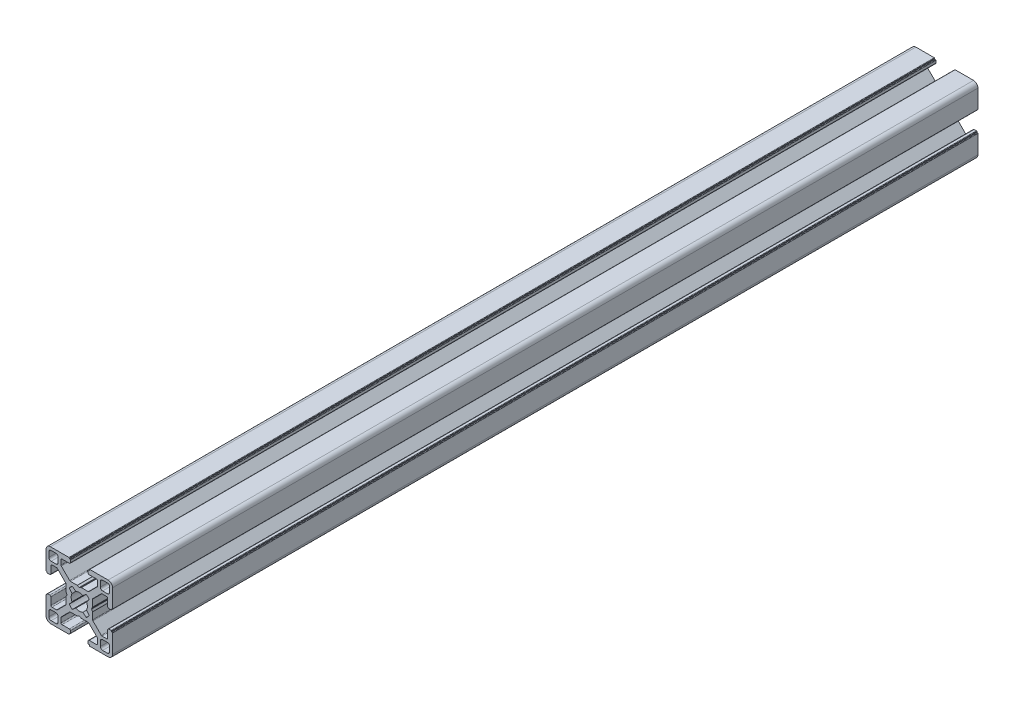
SolidWorks part; units mm, degrees
ref_plane "Alzado" through (0, 0, 0) normal (0, 0, 1) x (1, 0, 0)
ref_plane "Planta" through (0, 0, 0) normal (0, 1, 0) x (1, 0, 0)
ref_plane "Vista lateral" through (0, 0, 0) normal (1, 0, 0) x (0, 0, -1)
ref_plane "Plano1" through (0, 0, 1000) normal (0, 0, 1) x (1, 0, 0)
sketch "Croquis1" plane through (0, 0, 1000) normal (0, 0, 1) x (1, 0, 0)
  line L0 (8, -5.5) -> (5.8, -5.5)
  line L1 (4.8, -4.5) -> (4.8, -2.3)
  line L2 (5.8, -1.3) -> (8, -1.3)
  line L3 (9, -2.3) -> (9, -4.5)
  line L4 (-15.2, -5.5) -> (-17.4, -5.5)
  line L5 (-18.4, -4.5) -> (-18.4, -2.3)
  line L6 (-17.4, -1.3) -> (-15.2, -1.3)
  line L7 (-14.2, -2.3) -> (-14.2, -4.5)
  line L8 (-17.4, -24.5) -> (-15.2, -24.5)
  line L9 (-14.2, -25.5) -> (-14.2, -27.7)
  line L10 (-15.2, -28.7) -> (-17.4, -28.7)
  line L11 (-18.4, -27.7) -> (-18.4, -25.5)
  line L12 (5.8, -24.5) -> (8, -24.5)
  line L13 (9, -25.5) -> (9, -27.7)
  line L14 (8, -28.7) -> (5.8, -28.7)
  line L15 (4.8, -27.7) -> (4.8, -25.5)
  line L16 (-7.8359, -10.4816) -> (-6.3001, -11.7194)
  line L17 (-3.0999, -11.7194) -> (-1.5641, -10.4816)
  line L18 (-0.1947, -11.8453) -> (-1.4194, -13.3999)
  line L19 (-1.4194, -16.6001) -> (-0.1947, -18.1547)
  line L20 (-1.5641, -19.5184) -> (-3.0999, -18.2806)
  line L21 (-6.3001, -18.2806) -> (-7.8359, -19.5184)
  line L22 (-9.2053, -18.1547) -> (-7.9806, -16.6001)
  line L23 (-7.9806, -13.3999) -> (-9.2053, -11.8453)
  line L24 (9.8, -10.5) -> (10.1, -10.5)
  line L25 (10.3, -10.3) -> (10.3, -2)
  line L26 (8.3, 0) -> (0, 0)
  line L27 (-0.2, -0.2) -> (-0.2, -0.5)
  line L28 (-0.2, -0.5) -> (-0.5, -0.5)
  line L29 (-0.7, -0.7) -> (-0.7, -1.7)
  line L30 (-0.2, -2.2) -> (3.05, -2.2)
  line L31 (3.55, -2.7) -> (3.55, -4.7431)
  line L32 (3.4037, -5.0964) -> (-0.3491, -8.8534)
  line L33 (-0.7028, -9) -> (-3.7468, -9)
  line L34 (-3.8462, -9.0264) -> (-4.6006, -9.4583)
  line L35 (-4.7994, -9.4583) -> (-5.5538, -9.0264)
  line L36 (-5.6532, -9) -> (-8.6972, -9)
  line L37 (-9.0509, -8.8534) -> (-12.8037, -5.0964)
  line L38 (-12.95, -4.7431) -> (-12.95, -2.7)
  line L39 (-12.45, -2.2) -> (-9.2, -2.2)
  line L40 (-8.7, -1.7) -> (-8.7, -0.7)
  line L41 (-8.9, -0.5) -> (-9.2, -0.5)
  line L42 (-9.2, -0.5) -> (-9.2, -0.2)
  line L43 (-9.4, 0) -> (-17.7, 0)
  line L44 (-19.7, -2) -> (-19.7, -10.3)
  line L45 (-19.5, -10.5) -> (-19.2, -10.5)
  line L46 (-19.2, -10.5) -> (-19.2, -10.8)
  line L47 (-19, -11) -> (-18, -11)
  line L48 (-17.5, -10.5) -> (-17.5, -7.25)
  line L49 (-17, -6.75) -> (-14.9569, -6.75)
  line L50 (-14.6036, -6.8963) -> (-10.8466, -10.6491)
  line L51 (-10.7, -11.0028) -> (-10.7, -14.0468)
  line L52 (-10.6736, -14.1462) -> (-10.2417, -14.9006)
  line L53 (-10.2417, -15.0994) -> (-10.6736, -15.8538)
  line L54 (-10.7, -15.9532) -> (-10.7, -18.9972)
  line L55 (-10.8466, -19.3509) -> (-14.6036, -23.1037)
  line L56 (-14.9569, -23.25) -> (-17, -23.25)
  line L57 (-17.5, -22.75) -> (-17.5, -19.5)
  line L58 (-18, -19) -> (-19, -19)
  line L59 (-19.2, -19.2) -> (-19.2, -19.5)
  line L60 (-19.2, -19.5) -> (-19.5, -19.5)
  line L61 (-19.7, -19.7) -> (-19.7, -28)
  line L62 (-17.7, -30) -> (-9.4, -30)
  line L63 (-9.2, -29.8) -> (-9.2, -29.5)
  line L64 (-9.2, -29.5) -> (-8.9, -29.5)
  line L65 (-8.7, -29.3) -> (-8.7, -28.3)
  line L66 (-9.2, -27.8) -> (-12.45, -27.8)
  line L67 (-12.95, -27.3) -> (-12.95, -25.2569)
  line L68 (-12.8037, -24.9036) -> (-9.0509, -21.1466)
  line L69 (-8.6972, -21) -> (-5.6532, -21)
  line L70 (-5.5538, -20.9736) -> (-4.7994, -20.5417)
  line L71 (-4.6006, -20.5417) -> (-3.8462, -20.9736)
  line L72 (-3.7468, -21) -> (-0.7028, -21)
  line L73 (-0.3491, -21.1466) -> (3.4037, -24.9036)
  line L74 (3.55, -25.2569) -> (3.55, -27.3)
  line L75 (3.05, -27.8) -> (-0.2, -27.8)
  line L76 (-0.7, -28.3) -> (-0.7, -29.3)
  line L77 (-0.5, -29.5) -> (-0.2, -29.5)
  line L78 (-0.2, -29.5) -> (-0.2, -29.8)
  line L79 (0, -30) -> (8.3, -30)
  line L80 (10.3, -28) -> (10.3, -19.7)
  line L81 (10.1, -19.5) -> (9.8, -19.5)
  line L82 (9.8, -19.5) -> (9.8, -19.2)
  line L83 (9.6, -19) -> (8.6, -19)
  line L84 (8.1, -19.5) -> (8.1, -22.75)
  line L85 (7.6, -23.25) -> (5.5569, -23.25)
  line L86 (5.2036, -23.1037) -> (1.4466, -19.3509)
  line L87 (1.3, -18.9972) -> (1.3, -15.9532)
  line L88 (1.2736, -15.8538) -> (0.8417, -15.0994)
  line L89 (0.8417, -14.9006) -> (1.2736, -14.1462)
  line L90 (1.3, -14.0468) -> (1.3, -11.0028)
  line L91 (1.4466, -10.6491) -> (5.2036, -6.8963)
  line L92 (5.5569, -6.75) -> (7.6, -6.75)
  line L93 (8.1, -7.25) -> (8.1, -10.5)
  line L94 (8.6, -11) -> (9.6, -11)
  line L95 (9.8, -10.8) -> (9.8, -10.5)
  arc A0 (9, -4.5) -> (8, -5.5) centre (8, -4.5) cw
  arc A1 (5.8, -5.5) -> (4.8, -4.5) centre (5.8, -4.5) cw
  arc A2 (4.8, -2.3) -> (5.8, -1.3) centre (5.8, -2.3) cw
  arc A3 (8, -1.3) -> (9, -2.3) centre (8, -2.3) cw
  arc A4 (-14.2, -4.5) -> (-15.2, -5.5) centre (-15.2, -4.5) cw
  arc A5 (-17.4, -5.5) -> (-18.4, -4.5) centre (-17.4, -4.5) cw
  arc A6 (-18.4, -2.3) -> (-17.4, -1.3) centre (-17.4, -2.3) cw
  arc A7 (-15.2, -1.3) -> (-14.2, -2.3) centre (-15.2, -2.3) cw
  arc A8 (-18.4, -25.5) -> (-17.4, -24.5) centre (-17.4, -25.5) cw
  arc A9 (-15.2, -24.5) -> (-14.2, -25.5) centre (-15.2, -25.5) cw
  arc A10 (-14.2, -27.7) -> (-15.2, -28.7) centre (-15.2, -27.7) cw
  arc A11 (-17.4, -28.7) -> (-18.4, -27.7) centre (-17.4, -27.7) cw
  arc A12 (4.8, -25.5) -> (5.8, -24.5) centre (5.8, -25.5) cw
  arc A13 (8, -24.5) -> (9, -25.5) centre (8, -25.5) cw
  arc A14 (9, -27.7) -> (8, -28.7) centre (8, -27.7) cw
  arc A15 (5.8, -28.7) -> (4.8, -27.7) centre (5.8, -27.7) cw
  arc A16 (-9.2053, -11.8453) -> (-7.8359, -10.4816) centre (-4.7, -15) cw
  arc A17 (-6.3001, -11.7194) -> (-3.0999, -11.7194) centre (-4.7, -15) cw
  arc A18 (-1.5641, -10.4816) -> (-0.1947, -11.8453) centre (-4.7, -15) cw
  arc A19 (-1.4194, -13.3999) -> (-1.4194, -16.6001) centre (-4.7, -15) cw
  arc A20 (-0.1947, -18.1547) -> (-1.5641, -19.5184) centre (-4.7, -15) cw
  arc A21 (-3.0999, -18.2806) -> (-6.3001, -18.2806) centre (-4.7, -15) cw
  arc A22 (-7.8359, -19.5184) -> (-9.2053, -18.1547) centre (-4.7, -15) cw
  arc A23 (-7.9806, -16.6001) -> (-7.9806, -13.3999) centre (-4.7, -15) cw
  arc A24 (10.1, -10.5) -> (10.3, -10.3) centre (10.1, -10.3) ccw
  arc A25 (10.3, -2) -> (8.3, 0) centre (8.3, -2) ccw
  arc A26 (0, 0) -> (-0.2, -0.2) centre (0, -0.2) ccw
  arc A27 (-0.5, -0.5) -> (-0.7, -0.7) centre (-0.5, -0.7) ccw
  arc A28 (-0.7, -1.7) -> (-0.2, -2.2) centre (-0.2, -1.7) ccw
  arc A29 (3.05, -2.2) -> (3.55, -2.7) centre (3.05, -2.7) cw
  arc A30 (3.55, -4.7431) -> (3.4037, -5.0964) centre (3.05, -4.7431) cw
  arc A31 (-0.3491, -8.8534) -> (-0.7028, -9) centre (-0.7028, -8.5) cw
  arc A32 (-3.7468, -9) -> (-3.8462, -9.0264) centre (-3.7468, -9.2) ccw
  arc A33 (-4.6006, -9.4583) -> (-4.7994, -9.4583) centre (-4.7, -9.2847) cw
  arc A34 (-5.5538, -9.0264) -> (-5.6532, -9) centre (-5.6532, -9.2) ccw
  arc A35 (-8.6972, -9) -> (-9.0509, -8.8534) centre (-8.6972, -8.5) cw
  arc A36 (-12.8037, -5.0964) -> (-12.95, -4.7431) centre (-12.45, -4.7431) cw
  arc A37 (-12.95, -2.7) -> (-12.45, -2.2) centre (-12.45, -2.7) cw
  arc A38 (-9.2, -2.2) -> (-8.7, -1.7) centre (-9.2, -1.7) ccw
  arc A39 (-8.7, -0.7) -> (-8.9, -0.5) centre (-8.9, -0.7) ccw
  arc A40 (-9.2, -0.2) -> (-9.4, 0) centre (-9.4, -0.2) ccw
  arc A41 (-17.7, 0) -> (-19.7, -2) centre (-17.7, -2) ccw
  arc A42 (-19.7, -10.3) -> (-19.5, -10.5) centre (-19.5, -10.3) ccw
  arc A43 (-19.2, -10.8) -> (-19, -11) centre (-19, -10.8) ccw
  arc A44 (-18, -11) -> (-17.5, -10.5) centre (-18, -10.5) ccw
  arc A45 (-17.5, -7.25) -> (-17, -6.75) centre (-17, -7.25) cw
  arc A46 (-14.9569, -6.75) -> (-14.6036, -6.8963) centre (-14.9569, -7.25) cw
  arc A47 (-10.8466, -10.6491) -> (-10.7, -11.0028) centre (-11.2, -11.0028) cw
  arc A48 (-10.7, -14.0468) -> (-10.6736, -14.1462) centre (-10.5, -14.0468) ccw
  arc A49 (-10.2417, -14.9006) -> (-10.2417, -15.0994) centre (-10.4153, -15) cw
  arc A50 (-10.6736, -15.8538) -> (-10.7, -15.9532) centre (-10.5, -15.9532) ccw
  arc A51 (-10.7, -18.9972) -> (-10.8466, -19.3509) centre (-11.2, -18.9972) cw
  arc A52 (-14.6036, -23.1037) -> (-14.9569, -23.25) centre (-14.9569, -22.75) cw
  arc A53 (-17, -23.25) -> (-17.5, -22.75) centre (-17, -22.75) cw
  arc A54 (-17.5, -19.5) -> (-18, -19) centre (-18, -19.5) ccw
  arc A55 (-19, -19) -> (-19.2, -19.2) centre (-19, -19.2) ccw
  arc A56 (-19.5, -19.5) -> (-19.7, -19.7) centre (-19.5, -19.7) ccw
  arc A57 (-19.7, -28) -> (-17.7, -30) centre (-17.7, -28) ccw
  arc A58 (-9.4, -30) -> (-9.2, -29.8) centre (-9.4, -29.8) ccw
  arc A59 (-8.9, -29.5) -> (-8.7, -29.3) centre (-8.9, -29.3) ccw
  arc A60 (-8.7, -28.3) -> (-9.2, -27.8) centre (-9.2, -28.3) ccw
  arc A61 (-12.45, -27.8) -> (-12.95, -27.3) centre (-12.45, -27.3) cw
  arc A62 (-12.95, -25.2569) -> (-12.8037, -24.9036) centre (-12.45, -25.2569) cw
  arc A63 (-9.0509, -21.1466) -> (-8.6972, -21) centre (-8.6972, -21.5) cw
  arc A64 (-5.6532, -21) -> (-5.5538, -20.9736) centre (-5.6532, -20.8) ccw
  arc A65 (-4.7994, -20.5417) -> (-4.6006, -20.5417) centre (-4.7, -20.7153) cw
  arc A66 (-3.8462, -20.9736) -> (-3.7468, -21) centre (-3.7468, -20.8) ccw
  arc A67 (-0.7028, -21) -> (-0.3491, -21.1466) centre (-0.7028, -21.5) cw
  arc A68 (3.4037, -24.9036) -> (3.55, -25.2569) centre (3.05, -25.2569) cw
  arc A69 (3.55, -27.3) -> (3.05, -27.8) centre (3.05, -27.3) cw
  arc A70 (-0.2, -27.8) -> (-0.7, -28.3) centre (-0.2, -28.3) ccw
  arc A71 (-0.7, -29.3) -> (-0.5, -29.5) centre (-0.5, -29.3) ccw
  arc A72 (-0.2, -29.8) -> (0, -30) centre (0, -29.8) ccw
  arc A73 (8.3, -30) -> (10.3, -28) centre (8.3, -28) ccw
  arc A74 (10.3, -19.7) -> (10.1, -19.5) centre (10.1, -19.7) ccw
  arc A75 (9.8, -19.2) -> (9.6, -19) centre (9.6, -19.2) ccw
  arc A76 (8.6, -19) -> (8.1, -19.5) centre (8.6, -19.5) ccw
  arc A77 (8.1, -22.75) -> (7.6, -23.25) centre (7.6, -22.75) cw
  arc A78 (5.5569, -23.25) -> (5.2036, -23.1037) centre (5.5569, -22.75) cw
  arc A79 (1.4466, -19.3509) -> (1.3, -18.9972) centre (1.8, -18.9972) cw
  arc A80 (1.3, -15.9532) -> (1.2736, -15.8538) centre (1.1, -15.9532) ccw
  arc A81 (0.8417, -15.0994) -> (0.8417, -14.9006) centre (1.0153, -15) cw
  arc A82 (1.2736, -14.1462) -> (1.3, -14.0468) centre (1.1, -14.0468) ccw
  arc A83 (1.3, -11.0028) -> (1.4466, -10.6491) centre (1.8, -11.0028) cw
  arc A84 (5.2036, -6.8963) -> (5.5569, -6.75) centre (5.5569, -7.25) cw
  arc A85 (7.6, -6.75) -> (8.1, -7.25) centre (7.6, -7.25) cw
  arc A86 (8.1, -10.5) -> (8.6, -11) centre (8.6, -10.5) ccw
  arc A87 (9.6, -11) -> (9.8, -10.8) centre (9.6, -10.8) ccw
extrude "Saliente-Extruir1" add sketch "Croquis1" against normal blind 1000
sketch "Croquis4" plane through (0, 0, 0) normal (0, 0, -1) x (-1, 0, 0)
  line L72 (-9.8, -10.5) -> (-9.8, -10.8)
  line L73 (-9.6, -11) -> (-8.6, -11)
  line L74 (-8.1, -10.5) -> (-8.1, -7.25)
  line L75 (-7.6, -6.75) -> (-5.5569, -6.75)
  line L76 (-5.2036, -6.8963) -> (-1.4466, -10.6491)
  line L77 (-1.3, -11.0028) -> (-1.3, -14.0468)
  line L78 (-1.2736, -14.1462) -> (-0.8417, -14.9006)
  line L79 (-0.8417, -15.0994) -> (-1.2736, -15.8538)
  line L80 (-1.3, -15.9532) -> (-1.3, -18.9972)
  line L81 (-1.4466, -19.3509) -> (-5.2036, -23.1037)
  line L82 (-5.5569, -23.25) -> (-7.6, -23.25)
  line L83 (-8.1, -22.75) -> (-8.1, -19.5)
  line L84 (-8.6, -19) -> (-9.6, -19)
  line L85 (-9.8, -19.2) -> (-9.8, -19.5)
  line L86 (-9.8, -19.5) -> (-10.1, -19.5)
  line L87 (-10.3, -19.7) -> (-10.3, -28)
  line L88 (-8.3, -30) -> (0, -30)
  line L89 (0.2, -29.8) -> (0.2, -29.5)
  line L90 (0.2, -29.5) -> (0.5, -29.5)
  line L91 (0.7, -29.3) -> (0.7, -28.3)
  line L92 (0.2, -27.8) -> (-3.05, -27.8)
  line L93 (-3.55, -27.3) -> (-3.55, -25.2569)
  line L94 (-3.4037, -24.9036) -> (0.3491, -21.1466)
  line L95 (0.7028, -21) -> (3.7468, -21)
  line L96 (3.8462, -20.9736) -> (4.6006, -20.5417)
  line L97 (4.7994, -20.5417) -> (5.5538, -20.9736)
  line L98 (5.6532, -21) -> (8.6972, -21)
  line L99 (9.0509, -21.1466) -> (12.8037, -24.9036)
  line L100 (12.95, -25.2569) -> (12.95, -27.3)
  line L101 (12.45, -27.8) -> (9.2, -27.8)
  line L102 (8.7, -28.3) -> (8.7, -29.3)
  line L103 (8.9, -29.5) -> (9.2, -29.5)
  line L104 (9.2, -29.5) -> (9.2, -29.8)
  line L105 (9.4, -30) -> (17.7, -30)
  line L106 (19.7, -28) -> (19.7, -19.7)
  line L107 (19.5, -19.5) -> (19.2, -19.5)
  line L108 (19.2, -19.5) -> (19.2, -19.2)
  line L109 (19, -19) -> (18, -19)
  line L110 (17.5, -19.5) -> (17.5, -22.75)
  line L111 (17, -23.25) -> (14.9569, -23.25)
  line L112 (14.6036, -23.1037) -> (10.8466, -19.3509)
  line L113 (10.7, -18.9972) -> (10.7, -15.9532)
  line L114 (10.6736, -15.8538) -> (10.2417, -15.0994)
  line L115 (10.2417, -14.9006) -> (10.6736, -14.1462)
  line L116 (10.7, -14.0468) -> (10.7, -11.0028)
  line L117 (10.8466, -10.6491) -> (14.6036, -6.8963)
  line L118 (14.9569, -6.75) -> (17, -6.75)
  line L119 (17.5, -7.25) -> (17.5, -10.5)
  line L120 (18, -11) -> (19, -11)
  line L121 (19.2, -10.8) -> (19.2, -10.5)
  line L122 (19.2, -10.5) -> (19.5, -10.5)
  line L123 (19.7, -10.3) -> (19.7, -2)
  line L124 (17.7, 0) -> (9.4, 0)
  line L125 (9.2, -0.2) -> (9.2, -0.5)
  line L126 (9.2, -0.5) -> (8.9, -0.5)
  line L127 (8.7, -0.7) -> (8.7, -1.7)
  line L128 (9.2, -2.2) -> (12.45, -2.2)
  line L129 (12.95, -2.7) -> (12.95, -4.7431)
  line L130 (12.8037, -5.0964) -> (9.0509, -8.8534)
  line L131 (8.6972, -9) -> (5.6532, -9)
  line L132 (5.5538, -9.0264) -> (4.7994, -9.4583)
  line L133 (4.6006, -9.4583) -> (3.8462, -9.0264)
  line L134 (3.7468, -9) -> (0.7028, -9)
  line L135 (0.3491, -8.8534) -> (-3.4037, -5.0964)
  line L136 (-3.55, -4.7431) -> (-3.55, -2.7)
  line L137 (-3.05, -2.2) -> (0.2, -2.2)
  line L138 (0.7, -1.7) -> (0.7, -0.7)
  line L139 (0.5, -0.5) -> (0.2, -0.5)
  line L140 (0.2, -0.5) -> (0.2, -0.2)
  line L141 (0, 0) -> (-8.3, 0)
  line L142 (-10.3, -2) -> (-10.3, -10.3)
  line L143 (-10.1, -10.5) -> (-9.8, -10.5)
  line L144 (-9.8, -10.5) -> (-9.8, -10.8)
  line L145 (-9.6, -11) -> (-8.6, -11)
  line L146 (-8.1, -10.5) -> (-8.1, -7.25)
  line L147 (-7.6, -6.75) -> (-5.5569, -6.75)
  line L148 (-5.2036, -6.8963) -> (-1.4466, -10.6491)
  line L149 (-1.3, -11.0028) -> (-1.3, -14.0468)
  line L150 (-1.2736, -14.1462) -> (-0.8417, -14.9006)
  line L151 (-0.8417, -15.0994) -> (-1.2736, -15.8538)
  line L152 (-1.3, -15.9532) -> (-1.3, -18.9972)
  line L153 (-1.4466, -19.3509) -> (-5.2036, -23.1037)
  line L154 (-5.5569, -23.25) -> (-7.6, -23.25)
  line L155 (-8.1, -22.75) -> (-8.1, -19.5)
  line L156 (-8.6, -19) -> (-9.6, -19)
  line L157 (-9.8, -19.2) -> (-9.8, -19.5)
  line L158 (-9.8, -19.5) -> (-10.1, -19.5)
  line L159 (-10.3, -19.7) -> (-10.3, -28)
  line L160 (-8.3, -30) -> (0, -30)
  line L161 (0.2, -29.8) -> (0.2, -29.5)
  line L162 (0.2, -29.5) -> (0.5, -29.5)
  line L163 (0.7, -29.3) -> (0.7, -28.3)
  line L164 (0.2, -27.8) -> (-3.05, -27.8)
  line L165 (-3.55, -27.3) -> (-3.55, -25.2569)
  line L166 (-3.4037, -24.9036) -> (0.3491, -21.1466)
  line L167 (0.7028, -21) -> (3.7468, -21)
  line L168 (3.8462, -20.9736) -> (4.6006, -20.5417)
  line L169 (4.7994, -20.5417) -> (5.5538, -20.9736)
  line L170 (5.6532, -21) -> (8.6972, -21)
  line L171 (9.0509, -21.1466) -> (12.8037, -24.9036)
  line L172 (12.95, -25.2569) -> (12.95, -27.3)
  line L173 (12.45, -27.8) -> (9.2, -27.8)
  line L174 (8.7, -28.3) -> (8.7, -29.3)
  line L175 (8.9, -29.5) -> (9.2, -29.5)
  line L176 (9.2, -29.5) -> (9.2, -29.8)
  line L177 (9.4, -30) -> (17.7, -30)
  line L178 (19.7, -28) -> (19.7, -19.7)
  line L179 (19.5, -19.5) -> (19.2, -19.5)
  line L180 (19.2, -19.5) -> (19.2, -19.2)
  line L181 (19, -19) -> (18, -19)
  line L182 (17.5, -19.5) -> (17.5, -22.75)
  line L183 (17, -23.25) -> (14.9569, -23.25)
  line L184 (14.6036, -23.1037) -> (10.8466, -19.3509)
  line L185 (10.7, -18.9972) -> (10.7, -15.9532)
  line L186 (10.6736, -15.8538) -> (10.2417, -15.0994)
  line L187 (10.2417, -14.9006) -> (10.6736, -14.1462)
  line L188 (10.7, -14.0468) -> (10.7, -11.0028)
  line L189 (10.8466, -10.6491) -> (14.6036, -6.8963)
  line L190 (14.9569, -6.75) -> (17, -6.75)
  line L191 (17.5, -7.25) -> (17.5, -10.5)
  line L192 (18, -11) -> (19, -11)
  line L193 (19.2, -10.8) -> (19.2, -10.5)
  line L194 (19.2, -10.5) -> (19.5, -10.5)
  line L195 (19.7, -10.3) -> (19.7, -2)
  line L196 (17.7, 0) -> (9.4, 0)
  line L197 (9.2, -0.2) -> (9.2, -0.5)
  line L198 (9.2, -0.5) -> (8.9, -0.5)
  line L199 (8.7, -0.7) -> (8.7, -1.7)
  line L200 (9.2, -2.2) -> (12.45, -2.2)
  line L201 (12.95, -2.7) -> (12.95, -4.7431)
  line L202 (12.8037, -5.0964) -> (9.0509, -8.8534)
  line L203 (8.6972, -9) -> (5.6532, -9)
  line L204 (5.5538, -9.0264) -> (4.7994, -9.4583)
  line L205 (4.6006, -9.4583) -> (3.8462, -9.0264)
  line L206 (3.7468, -9) -> (0.7028, -9)
  line L207 (0.3491, -8.8534) -> (-3.4037, -5.0964)
  line L208 (-3.55, -4.7431) -> (-3.55, -2.7)
  line L209 (-3.05, -2.2) -> (0.2, -2.2)
  line L210 (0.7, -1.7) -> (0.7, -0.7)
  line L211 (0.5, -0.5) -> (0.2, -0.5)
  line L212 (0.2, -0.5) -> (0.2, -0.2)
  line L213 (0, 0) -> (-8.3, 0)
  line L214 (-10.3, -2) -> (-10.3, -10.3)
  line L215 (-10.1, -10.5) -> (-9.8, -10.5)
  arc A64 (-9.8, -10.8) -> (-9.6, -11) centre (-9.6, -10.8) ccw
  arc A65 (-8.6, -11) -> (-8.1, -10.5) centre (-8.6, -10.5) ccw
  arc A66 (-7.6, -6.75) -> (-8.1, -7.25) centre (-7.6, -7.25) ccw
  arc A67 (-5.2036, -6.8963) -> (-5.5569, -6.75) centre (-5.5569, -7.25) ccw
  arc A68 (-1.3, -11.0028) -> (-1.4466, -10.6491) centre (-1.8, -11.0028) ccw
  arc A69 (-1.3, -14.0468) -> (-1.2736, -14.1462) centre (-1.1, -14.0468) ccw
  arc A70 (-0.8417, -15.0994) -> (-0.8417, -14.9006) centre (-1.0153, -15) ccw
  arc A71 (-1.2736, -15.8538) -> (-1.3, -15.9532) centre (-1.1, -15.9532) ccw
  arc A72 (-1.4466, -19.3509) -> (-1.3, -18.9972) centre (-1.8, -18.9972) ccw
  arc A73 (-5.5569, -23.25) -> (-5.2036, -23.1037) centre (-5.5569, -22.75) ccw
  arc A74 (-8.1, -22.75) -> (-7.6, -23.25) centre (-7.6, -22.75) ccw
  arc A75 (-8.1, -19.5) -> (-8.6, -19) centre (-8.6, -19.5) ccw
  arc A76 (-9.6, -19) -> (-9.8, -19.2) centre (-9.6, -19.2) ccw
  arc A77 (-10.1, -19.5) -> (-10.3, -19.7) centre (-10.1, -19.7) ccw
  arc A78 (-10.3, -28) -> (-8.3, -30) centre (-8.3, -28) ccw
  arc A79 (0, -30) -> (0.2, -29.8) centre (0, -29.8) ccw
  arc A80 (0.5, -29.5) -> (0.7, -29.3) centre (0.5, -29.3) ccw
  arc A81 (0.7, -28.3) -> (0.2, -27.8) centre (0.2, -28.3) ccw
  arc A82 (-3.55, -27.3) -> (-3.05, -27.8) centre (-3.05, -27.3) ccw
  arc A83 (-3.4037, -24.9036) -> (-3.55, -25.2569) centre (-3.05, -25.2569) ccw
  arc A84 (0.7028, -21) -> (0.3491, -21.1466) centre (0.7028, -21.5) ccw
  arc A85 (3.7468, -21) -> (3.8462, -20.9736) centre (3.7468, -20.8) ccw
  arc A86 (4.7994, -20.5417) -> (4.6006, -20.5417) centre (4.7, -20.7153) ccw
  arc A87 (5.5538, -20.9736) -> (5.6532, -21) centre (5.6532, -20.8) ccw
  arc A88 (9.0509, -21.1466) -> (8.6972, -21) centre (8.6972, -21.5) ccw
  arc A89 (12.95, -25.2569) -> (12.8037, -24.9036) centre (12.45, -25.2569) ccw
  arc A90 (12.45, -27.8) -> (12.95, -27.3) centre (12.45, -27.3) ccw
  arc A91 (9.2, -27.8) -> (8.7, -28.3) centre (9.2, -28.3) ccw
  arc A92 (8.7, -29.3) -> (8.9, -29.5) centre (8.9, -29.3) ccw
  arc A93 (9.2, -29.8) -> (9.4, -30) centre (9.4, -29.8) ccw
  arc A94 (17.7, -30) -> (19.7, -28) centre (17.7, -28) ccw
  arc A95 (19.7, -19.7) -> (19.5, -19.5) centre (19.5, -19.7) ccw
  arc A96 (19.2, -19.2) -> (19, -19) centre (19, -19.2) ccw
  arc A97 (18, -19) -> (17.5, -19.5) centre (18, -19.5) ccw
  arc A98 (17, -23.25) -> (17.5, -22.75) centre (17, -22.75) ccw
  arc A99 (14.6036, -23.1037) -> (14.9569, -23.25) centre (14.9569, -22.75) ccw
  arc A100 (10.7, -18.9972) -> (10.8466, -19.3509) centre (11.2, -18.9972) ccw
  arc A101 (10.7, -15.9532) -> (10.6736, -15.8538) centre (10.5, -15.9532) ccw
  arc A102 (10.2417, -14.9006) -> (10.2417, -15.0994) centre (10.4153, -15) ccw
  arc A103 (10.6736, -14.1462) -> (10.7, -14.0468) centre (10.5, -14.0468) ccw
  arc A104 (10.8466, -10.6491) -> (10.7, -11.0028) centre (11.2, -11.0028) ccw
  arc A105 (14.9569, -6.75) -> (14.6036, -6.8963) centre (14.9569, -7.25) ccw
  arc A106 (17.5, -7.25) -> (17, -6.75) centre (17, -7.25) ccw
  arc A107 (17.5, -10.5) -> (18, -11) centre (18, -10.5) ccw
  arc A108 (19, -11) -> (19.2, -10.8) centre (19, -10.8) ccw
  arc A109 (19.5, -10.5) -> (19.7, -10.3) centre (19.5, -10.3) ccw
  arc A110 (19.7, -2) -> (17.7, 0) centre (17.7, -2) ccw
  arc A111 (9.4, 0) -> (9.2, -0.2) centre (9.4, -0.2) ccw
  arc A112 (8.9, -0.5) -> (8.7, -0.7) centre (8.9, -0.7) ccw
  arc A113 (8.7, -1.7) -> (9.2, -2.2) centre (9.2, -1.7) ccw
  arc A114 (12.95, -2.7) -> (12.45, -2.2) centre (12.45, -2.7) ccw
  arc A115 (12.8037, -5.0964) -> (12.95, -4.7431) centre (12.45, -4.7431) ccw
  arc A116 (8.6972, -9) -> (9.0509, -8.8534) centre (8.6972, -8.5) ccw
  arc A117 (5.6532, -9) -> (5.5538, -9.0264) centre (5.6532, -9.2) ccw
  arc A118 (4.6006, -9.4583) -> (4.7994, -9.4583) centre (4.7, -9.2847) ccw
  arc A119 (3.8462, -9.0264) -> (3.7468, -9) centre (3.7468, -9.2) ccw
  arc A120 (0.3491, -8.8534) -> (0.7028, -9) centre (0.7028, -8.5) ccw
  arc A121 (-3.55, -4.7431) -> (-3.4037, -5.0964) centre (-3.05, -4.7431) ccw
  arc A122 (-3.05, -2.2) -> (-3.55, -2.7) centre (-3.05, -2.7) ccw
  arc A123 (0.2, -2.2) -> (0.7, -1.7) centre (0.2, -1.7) ccw
  arc A124 (0.7, -0.7) -> (0.5, -0.5) centre (0.5, -0.7) ccw
  arc A125 (0.2, -0.2) -> (0, 0) centre (0, -0.2) ccw
  arc A126 (-8.3, 0) -> (-10.3, -2) centre (-8.3, -2) ccw
  arc A127 (-10.3, -10.3) -> (-10.1, -10.5) centre (-10.1, -10.3) ccw
  arc A128 (-9.8, -10.8) -> (-9.6, -11) centre (-9.6, -10.8) ccw
  arc A129 (-8.6, -11) -> (-8.1, -10.5) centre (-8.6, -10.5) ccw
  arc A130 (-7.6, -6.75) -> (-8.1, -7.25) centre (-7.6, -7.25) ccw
  arc A131 (-5.2036, -6.8963) -> (-5.5569, -6.75) centre (-5.5569, -7.25) ccw
  arc A132 (-1.3, -11.0028) -> (-1.4466, -10.6491) centre (-1.8, -11.0028) ccw
  arc A133 (-1.3, -14.0468) -> (-1.2736, -14.1462) centre (-1.1, -14.0468) ccw
  arc A134 (-0.8417, -15.0994) -> (-0.8417, -14.9006) centre (-1.0153, -15) ccw
  arc A135 (-1.2736, -15.8538) -> (-1.3, -15.9532) centre (-1.1, -15.9532) ccw
  arc A136 (-1.4466, -19.3509) -> (-1.3, -18.9972) centre (-1.8, -18.9972) ccw
  arc A137 (-5.5569, -23.25) -> (-5.2036, -23.1037) centre (-5.5569, -22.75) ccw
  arc A138 (-8.1, -22.75) -> (-7.6, -23.25) centre (-7.6, -22.75) ccw
  arc A139 (-8.1, -19.5) -> (-8.6, -19) centre (-8.6, -19.5) ccw
  arc A140 (-9.6, -19) -> (-9.8, -19.2) centre (-9.6, -19.2) ccw
  arc A141 (-10.1, -19.5) -> (-10.3, -19.7) centre (-10.1, -19.7) ccw
  arc A142 (-10.3, -28) -> (-8.3, -30) centre (-8.3, -28) ccw
  arc A143 (0, -30) -> (0.2, -29.8) centre (0, -29.8) ccw
  arc A144 (0.5, -29.5) -> (0.7, -29.3) centre (0.5, -29.3) ccw
  arc A145 (0.7, -28.3) -> (0.2, -27.8) centre (0.2, -28.3) ccw
  arc A146 (-3.55, -27.3) -> (-3.05, -27.8) centre (-3.05, -27.3) ccw
  arc A147 (-3.4037, -24.9036) -> (-3.55, -25.2569) centre (-3.05, -25.2569) ccw
  arc A148 (0.7028, -21) -> (0.3491, -21.1466) centre (0.7028, -21.5) ccw
  arc A149 (3.7468, -21) -> (3.8462, -20.9736) centre (3.7468, -20.8) ccw
  arc A150 (4.7994, -20.5417) -> (4.6006, -20.5417) centre (4.7, -20.7153) ccw
  arc A151 (5.5538, -20.9736) -> (5.6532, -21) centre (5.6532, -20.8) ccw
  arc A152 (9.0509, -21.1466) -> (8.6972, -21) centre (8.6972, -21.5) ccw
  arc A153 (12.95, -25.2569) -> (12.8037, -24.9036) centre (12.45, -25.2569) ccw
  arc A154 (12.45, -27.8) -> (12.95, -27.3) centre (12.45, -27.3) ccw
  arc A155 (9.2, -27.8) -> (8.7, -28.3) centre (9.2, -28.3) ccw
  arc A156 (8.7, -29.3) -> (8.9, -29.5) centre (8.9, -29.3) ccw
  arc A157 (9.2, -29.8) -> (9.4, -30) centre (9.4, -29.8) ccw
  arc A158 (17.7, -30) -> (19.7, -28) centre (17.7, -28) ccw
  arc A159 (19.7, -19.7) -> (19.5, -19.5) centre (19.5, -19.7) ccw
  arc A160 (19.2, -19.2) -> (19, -19) centre (19, -19.2) ccw
  arc A161 (18, -19) -> (17.5, -19.5) centre (18, -19.5) ccw
  arc A162 (17, -23.25) -> (17.5, -22.75) centre (17, -22.75) ccw
  arc A163 (14.6036, -23.1037) -> (14.9569, -23.25) centre (14.9569, -22.75) ccw
  arc A164 (10.7, -18.9972) -> (10.8466, -19.3509) centre (11.2, -18.9972) ccw
  arc A165 (10.7, -15.9532) -> (10.6736, -15.8538) centre (10.5, -15.9532) ccw
  arc A166 (10.2417, -14.9006) -> (10.2417, -15.0994) centre (10.4153, -15) ccw
  arc A167 (10.6736, -14.1462) -> (10.7, -14.0468) centre (10.5, -14.0468) ccw
  arc A168 (10.8466, -10.6491) -> (10.7, -11.0028) centre (11.2, -11.0028) ccw
  arc A169 (14.9569, -6.75) -> (14.6036, -6.8963) centre (14.9569, -7.25) ccw
  arc A170 (17.5, -7.25) -> (17, -6.75) centre (17, -7.25) ccw
  arc A171 (17.5, -10.5) -> (18, -11) centre (18, -10.5) ccw
  arc A172 (19, -11) -> (19.2, -10.8) centre (19, -10.8) ccw
  arc A173 (19.5, -10.5) -> (19.7, -10.3) centre (19.5, -10.3) ccw
  arc A174 (19.7, -2) -> (17.7, 0) centre (17.7, -2) ccw
  arc A175 (9.4, 0) -> (9.2, -0.2) centre (9.4, -0.2) ccw
  arc A176 (8.9, -0.5) -> (8.7, -0.7) centre (8.9, -0.7) ccw
  arc A177 (8.7, -1.7) -> (9.2, -2.2) centre (9.2, -1.7) ccw
  arc A178 (12.95, -2.7) -> (12.45, -2.2) centre (12.45, -2.7) ccw
  arc A179 (12.8037, -5.0964) -> (12.95, -4.7431) centre (12.45, -4.7431) ccw
  arc A180 (8.6972, -9) -> (9.0509, -8.8534) centre (8.6972, -8.5) ccw
  arc A181 (5.6532, -9) -> (5.5538, -9.0264) centre (5.6532, -9.2) ccw
  arc A182 (4.6006, -9.4583) -> (4.7994, -9.4583) centre (4.7, -9.2847) ccw
  arc A183 (3.8462, -9.0264) -> (3.7468, -9) centre (3.7468, -9.2) ccw
  arc A184 (0.3491, -8.8534) -> (0.7028, -9) centre (0.7028, -8.5) ccw
  arc A185 (-3.55, -4.7431) -> (-3.4037, -5.0964) centre (-3.05, -4.7431) ccw
  arc A186 (-3.05, -2.2) -> (-3.55, -2.7) centre (-3.05, -2.7) ccw
  arc A187 (0.2, -2.2) -> (0.7, -1.7) centre (0.2, -1.7) ccw
  arc A188 (0.7, -0.7) -> (0.5, -0.5) centre (0.5, -0.7) ccw
  arc A189 (0.2, -0.2) -> (0, 0) centre (0, -0.2) ccw
  arc A190 (-8.3, 0) -> (-10.3, -2) centre (-8.3, -2) ccw
  arc A191 (-10.3, -10.3) -> (-10.1, -10.5) centre (-10.1, -10.3) ccw
  dimension "D1" = 0
extrude "Cortar-Extruir1" cut sketch "Croquis4" against normal blind 610
